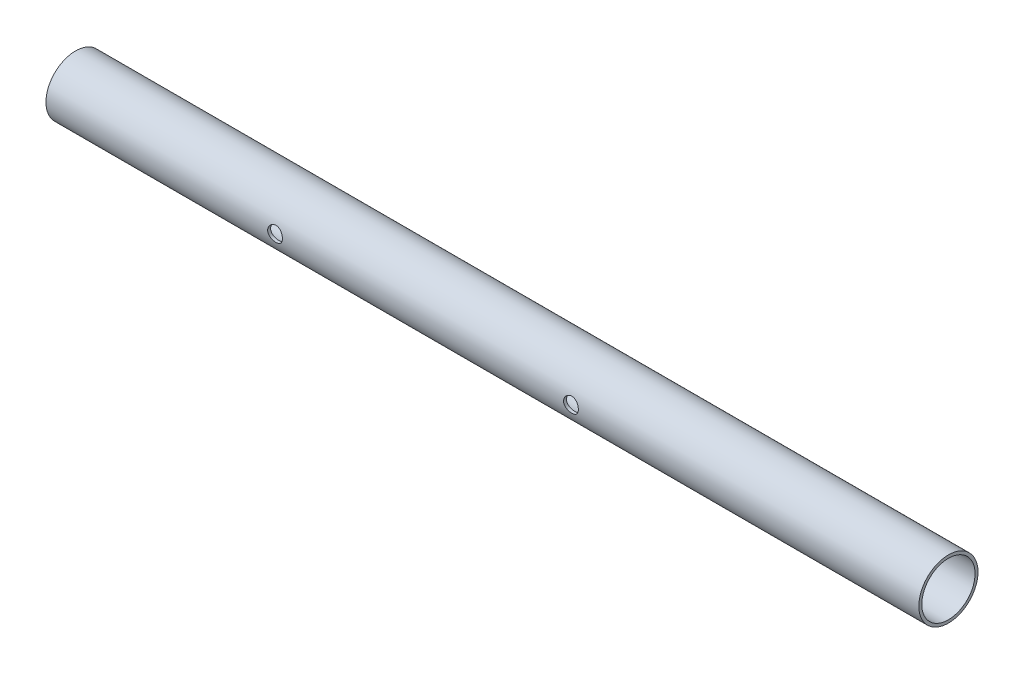
SolidWorks part; units mm, degrees
ref_plane "Front Plane" through (0, 0, 0) normal (0, 0, 1) x (1, 0, 0)
ref_plane "Top Plane" through (0, 0, 0) normal (0, 1, 0) x (1, 0, 0)
ref_plane "Right Plane" through (0, 0, 0) normal (1, 0, 0) x (0, 0, -1)
sketch "Sketch1" plane through (0, 0, 0) normal (1, 0, 0) x (0, 0, -1)
  circle A0 centre (0, 0) radius 20
  dimension "D1" = 40
extrude "Boss-Extrude1" add sketch "Sketch1" along normal blind 590
sketch "Sketch2" plane through (590, 0, 0) normal (1, 0, 0) x (0, 0, -1)
  circle A0 centre (0, 0) radius 18
  dimension "D1" = 36
extrude "Cut-Extrude1" cut sketch "Sketch2" against normal blind 602
sketch "Sketch3" plane through (0, 0, 0) normal (0, 0, 1) x (1, 0, 0)
  circle A0 centre (154.8553, 0) radius 5
  circle A1 centre (354.8553, 0) radius 5
  point P7 (237.655, -20)
  dimension "D1" = 10
  dimension "D2" = 10
  dimension "D3" = 154.8553
  dimension "D4" = 200
extrude "Cut-Extrude2" cut sketch "Sketch3" against normal through all both and the other way through all
